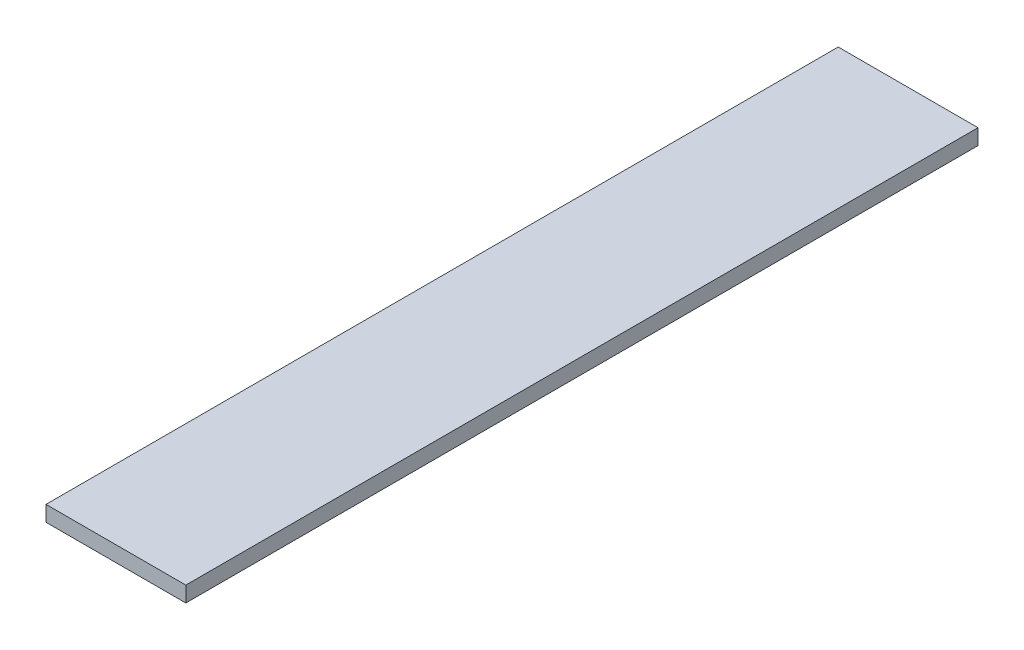
SolidWorks part; units mm, degrees
ref_plane "Front Plane" through (0, 0, 0) normal (0, 0, 1) x (1, 0, 0)
ref_plane "Top Plane" through (0, 0, 0) normal (0, 1, 0) x (1, 0, 0)
ref_plane "Right Plane" through (0, 0, 0) normal (1, 0, 0) x (0, 0, -1)
sketch "Sketch1" plane through (0, 0, 0) normal (0, 1, 0) x (1, 0, 0)
  line L1 (-57.15, 323.85) -> (57.15, 323.85)
  line L2 (-57.15, 323.85) -> (-57.15, -323.85)
  line L3 (-57.15, -323.85) -> (57.15, -323.85)
  line L4 (57.15, 323.85) -> (57.15, -323.85)
  line L5 (-57.15, 323.85) -> (57.15, -323.85) construction
  line L6 (-57.15, -323.85) -> (57.15, 323.85) construction
  point P0 (0, 0)
  dimension "D1" = 647.7
  dimension "D2" = 114.3
extrude "Boss-Extrude1" add sketch "Sketch1" along normal blind 12.7
